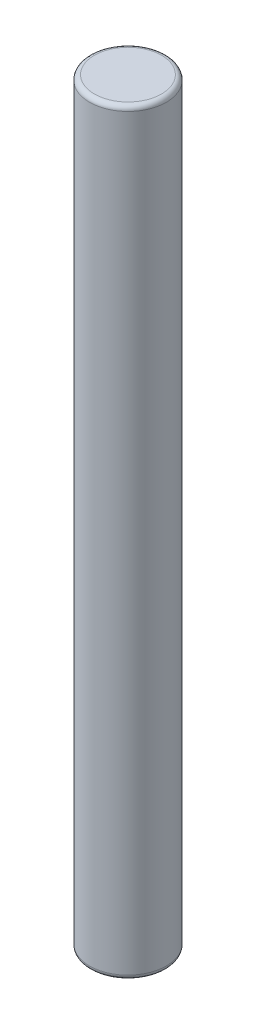
SolidWorks part; units mm, degrees
material "AISI 304"
ref_plane "Front Plane" through (0, 0, 0) normal (0, 0, 1) x (1, 0, 0)
ref_plane "Top Plane" through (0, 0, 0) normal (0, 1, 0) x (1, 0, 0)
ref_plane "Right Plane" through (0, 0, 0) normal (1, 0, 0) x (0, 0, -1)
sketch "Sketch1" plane through (0, 0, 0) normal (0, 1, 0) x (1, 0, 0)
  circle A0 centre (0, 0) radius 2
  dimension "D1" = 4
extrude "Boss-Extrude1" add sketch "Sketch1" along normal blind 39.5 contours A0
fillet "Fillet1" radius 0.25 2 edges at (0, 0, 2) (0, 39.5, 2)
